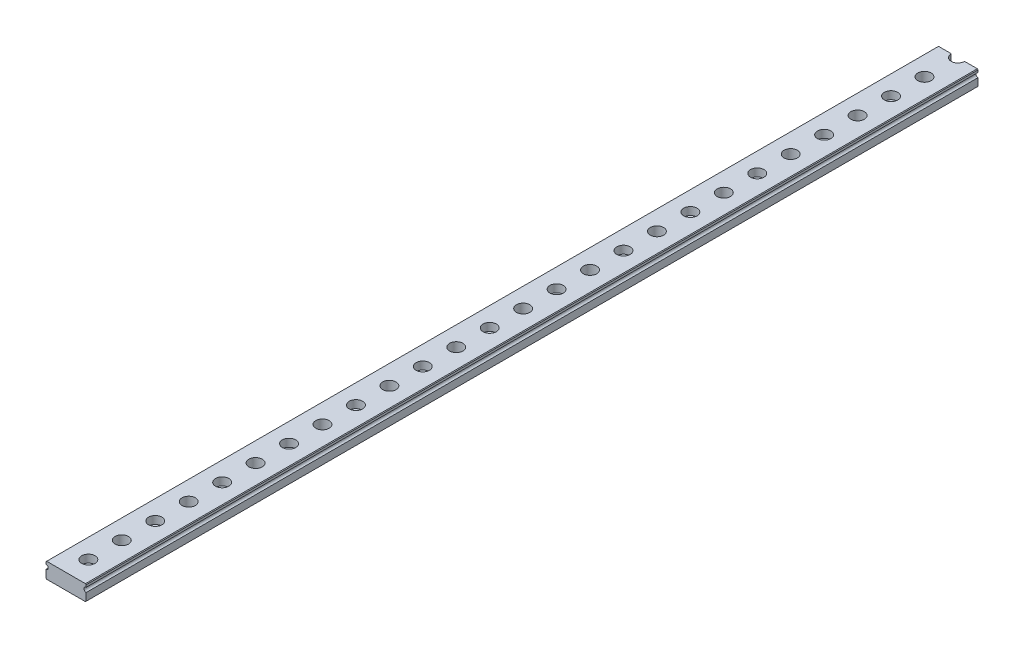
SolidWorks part; units mm, degrees
material "AISI 1020"
ref_plane "Front Plane" through (0, 0, 0) normal (0, 0, 1) x (1, 0, 0)
ref_plane "Top Plane" through (0, 0, 0) normal (0, 1, 0) x (1, 0, 0)
ref_plane "Right Plane" through (0, 0, 0) normal (1, 0, 0) x (0, 0, -1)
ref_plane "Plano1" through (0, 0, 0) normal (0, -1, 0) x (1, 0, 0)
sketch "Esboço1" plane through (0, 0, 0) normal (0, -1, 0) x (1, 0, 0)
  line L0 (-9, -200) -> (9, -200)
  line L1 (9, -200) -> (9, 200)
  line L2 (9, 200) -> (-9, 200)
  line L3 (-9, 200) -> (-9, -200)
  line L4 (0, 200) -> (0, -200) construction
  line L5 (-9, 0) -> (9, 0) construction
  point P9 (0, 0)
  dimension "D1" = 400
  dimension "D2" = 18
extrude "Ressalto-extrusão1" add sketch "Esboço1" against normal mid plane 7
hole_wizard "Furo de diâmetro Ø2.0 (2)1" positions "Esboço5" profile "Esboço4" hole size "Ø2.0" standard "Ansi Metric" end condition through all
sketch "Esboço5" plane through (0, 0, -200) normal (0, 0, -1) x (-1, 0, 0)
  line L0 (-9, -3.5) -> (9, -3.5) construction
  line L1 (9, 3.5) -> (9, -3.5) construction
  point P0 (-8.6691, 4.6357)
  point P1 (9, 1.2)
  dimension "D1" = 18
  dimension "D2" = 4.7
sketch "Esboço4" plane through (8.6691, 4.6357, -200) normal (1, 0, 0) x (0, 1, 0)
  line L0 (0, 0) -> (0, 400)
  line L1 (0, 400) -> (1, 400)
  line L2 (1, 400) -> (1, 0)
  line L5 (1, 0) -> (0, 0)
  line L11 (0, -6.35) -> (0, 107.95) construction
  dimension "Thru Hole Dia." = 2
  dimension "Thru Hole Depth" = 400
hole_wizard "Furo de diâmetro Ø6.0 (6)1" positions "Esboço3" profile "Esboço2" hole size "Ø6.0" standard "Ansi Metric" end condition through all
sketch "Esboço3" plane through (0, 3.5, 0) normal (0, 1, 0) x (1, 0, 0)
  line L0 (9, 200) -> (9, -200) construction
  line L1 (9, -200) -> (-9, -200) construction
  point P0 (0, -175)
  dimension "D3" = 9
  dimension "D4" = 25
sketch "Esboço2" plane through (0, 3.5, 175) normal (1, 0, 0) x (0, 0, 1)
  line L0 (0, 0) -> (0, 7)
  line L1 (0, 7) -> (3, 7)
  line L2 (3, 7) -> (3, 0)
  line L5 (3, 0) -> (0, 0)
  line L11 (0, -6.35) -> (0, 107.95) construction
  dimension "Thru Hole Dia." = 6
  dimension "Thru Hole Depth" = 7
hole_wizard "Rebaixo para parafuso de máquina de cabeça sextavada de M31" positions "Esboço9" profile "Esboço8" counterbore size "M3" standard "Ansi Metric" end condition through all
sketch "Esboço9" plane through (0, 3.5, 0) normal (0, 1, 0) x (1, 0, 0)
  line L0 (9, 200) -> (9, -200) construction
  line L3 (9, -200) -> (-9, -200) construction
  point P2 (0, -190)
  dimension "D3" = 9
  dimension "D6" = 10
sketch "Esboço8" plane through (0, 3.5, 190) normal (1, 0, 0) x (0, 0, 1)
  line L0 (0, 0) -> (0, 7)
  line L1 (0, 7) -> (1.75, 7)
  line L3 (1.75, 7) -> (1.75, 3.5)
  line L4 (1.75, 3.5) -> (3, 3.5)
  line L5 (3, 3.5) -> (3, 0)
  line L7 (3, 0) -> (0, 0)
  line L11 (0, -6.35) -> (0, 107.95) construction
  dimension "Thru Hole Dia." = 3.5
  dimension "Thru Hole Depth" = 7
  dimension "C'Bore Dia." = 6
  dimension "C'Bore Depth" = 3.5
pattern_linear "Padrão linear1" count 13 spacing 30 along (0, 0, -1) of "Furo de diâmetro Ø6.0 (6)1"
pattern_linear "Padrão linear2" count 14 spacing 30 along (0, 0, -1) of "Rebaixo para parafuso de máquina de cabeça sextavada de M31"
chamfer "Chanfro1" distance 0.3 angle 45 4 edges at (-9, 3.5, 0) (9, 3.5, 0) (9, -3.5, 0) (-9, -3.5, 0)
ref_plane "Plane1" through (0, 0, 0) normal (1, 0, 0) x (0, 0, -1)
ref_plane "Plane2" through (0, 0, 0) normal (0, 0, -1) x (-1, 0, 0)
mirror "Mirror1" about plane through (0, 0, 0) normal (1, 0, 0) of "Furo de diâmetro Ø2.0 (2)1"
